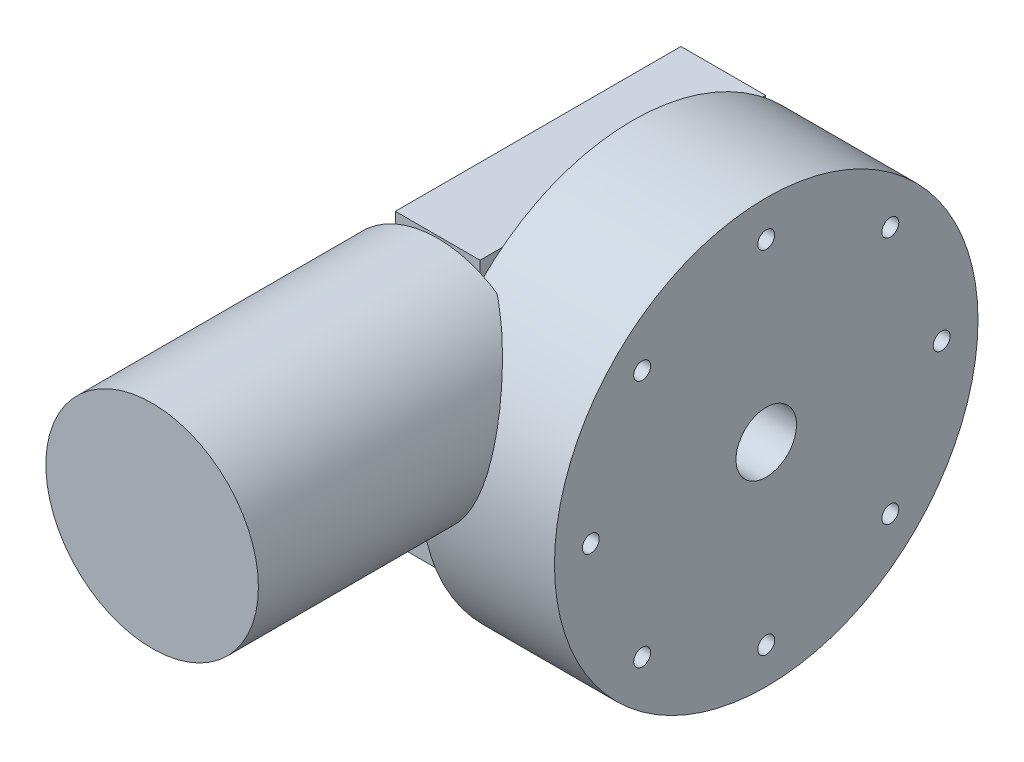
SolidWorks part; units mm, degrees
material "Malleable Cast Iron"
ref_plane "Front Plane" through (0, 0, 0) normal (0, 0, 1) x (1, 0, 0)
ref_plane "Top Plane" through (0, 0, 0) normal (0, 1, 0) x (1, 0, 0)
ref_plane "Right Plane" through (0, 0, 0) normal (1, 0, 0) x (0, 0, -1)
sketch "Sketch1" plane through (0, 0, 0) normal (1, 0, 0) x (0, 0, -1)
  circle A0 centre (0, 0) radius 175
  dimension "D1" = 350
extrude "Boss-Extrude1" add sketch "Sketch1" along normal blind 110.5
sketch "Sketch2" plane through (0, 0, 0) normal (-1, 0, 0) x (0, 0, 1)
  circle A0 centre (0, 0) radius 145 construction
  circle A1 centre (0, 145) radius 7
  point P5 (0, 0)
  dimension "D1" = 290
  dimension "D2" = 14
extrude "Cut-Extrude1" cut sketch "Sketch2" against normal through all
pattern_circular "CirPattern1" count 8 over 360 about axis through (0, 0, 0) along (1, 0, 0) of "Cut-Extrude1"
sketch "Sketch4" plane through (0, 0, 0) normal (1, 0, 0) x (0, 0, -1)
  line L1 (110, -100.5235) -> (-126, -100.5235)
  line L2 (110, -100.5235) -> (110, 138)
  line L3 (110, 138) -> (-126, 138)
  line L4 (-126, -100.5235) -> (-126, 138)
  dimension "D1" = 110
  dimension "D2" = 126
  dimension "D3" = 138
extrude "Boss-Extrude2" add sketch "Sketch4" against normal blind 70 separate body
sketch "Sketch5" plane through (0, 0, 126) normal (0, 0, 1) x (1, 0, 0)
  line L0 (-70, 138) -> (0, 138) construction
  circle A0 centre (-35, 48.3972) radius 87.8281
  point P5 (-35, 138)
  dimension "D1" = 175.6561
extrude "Boss-Extrude3" add sketch "Sketch5" along normal blind 236
sketch "Sketch6" plane through (110.5, 0, 0) normal (1, 0, 0) x (0, 0, -1)
  circle A0 centre (0, 0) radius 25
  dimension "D1" = 50
extrude "Cut-Extrude2" cut sketch "Sketch6" against normal through all
